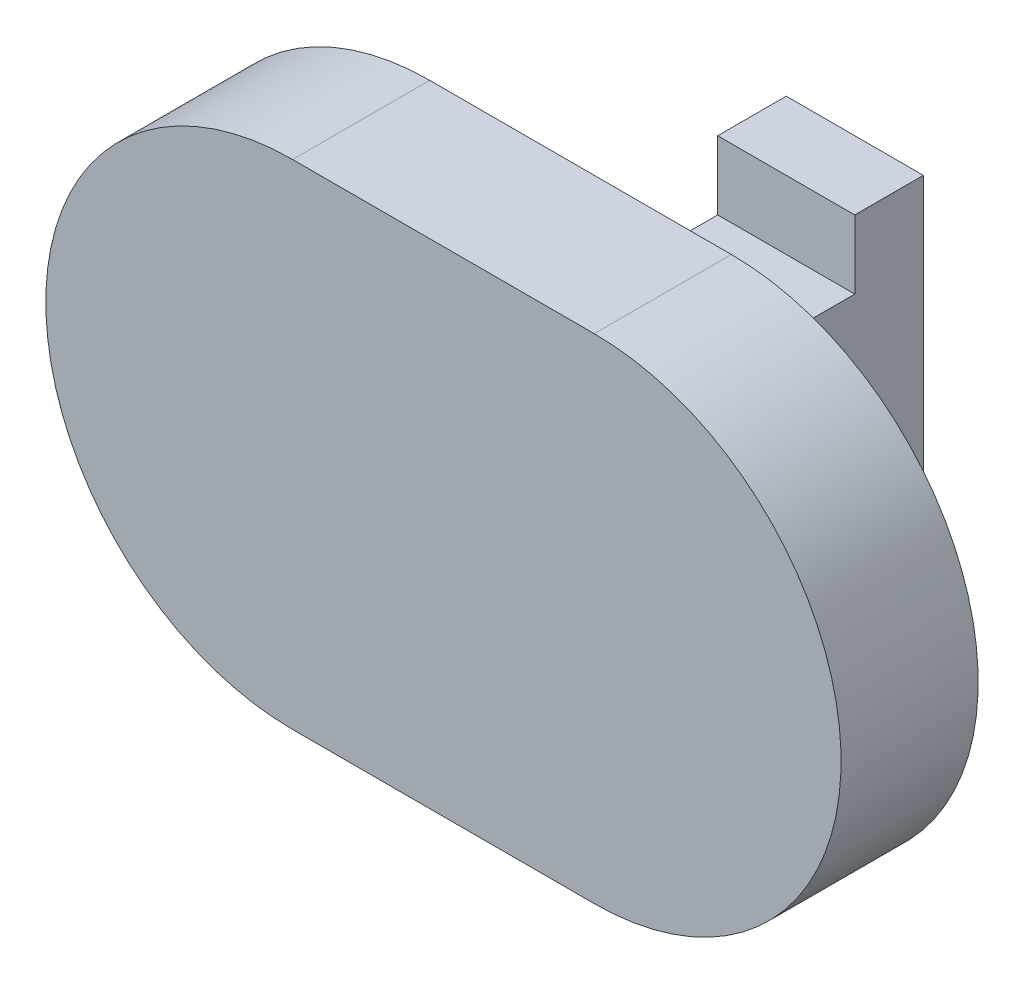
SolidWorks part; units mm, degrees
material "PVC Rigid"
ref_plane "Front Plane" through (0, 0, 0) normal (0, 0, 1) x (1, 0, 0)
ref_plane "Top Plane" through (0, 0, 0) normal (0, 1, 0) x (1, 0, 0)
ref_plane "Right Plane" through (0, 0, 0) normal (1, 0, 0) x (0, 0, -1)
sketch "Sketch3" plane through (0, 0, 0) normal (0, 0, 1) x (1, 0, 0)
  line L0 (-1.397, 0) -> (1.397, 0) construction
  line L1 (-1.397, 2.286) -> (1.397, 2.286)
  line L2 (-1.397, -2.286) -> (1.397, -2.286)
  arc A0 (-1.397, 2.286) -> (-1.397, -2.286) centre (-1.397, 0) ccw
  arc A1 (1.397, -2.286) -> (1.397, 2.286) centre (1.397, 0) ccw
  point P2 (0, 0)
  dimension "D1" = 2.286
  dimension "D2" = 2.794
extrude "Boss-Extrude1" add sketch "Sketch3" against normal blind 1.27
sketch "Sketch5" plane through (0, 0, -1.27) normal (0, 0, -1) x (-1, 0, 0)
  line L1 (0.635, 0.635) -> (-0.635, 0.635)
  line L2 (0.635, 0.635) -> (0.635, -0.635)
  line L3 (0.635, -0.635) -> (-0.635, -0.635)
  line L4 (-0.635, 0.635) -> (-0.635, -0.635)
  line L5 (0.635, 0.635) -> (-0.635, -0.635) construction
  line L6 (0.635, -0.635) -> (-0.635, 0.635) construction
  point P0 (0, 0)
  dimension "D1" = 1.27
  dimension "D2" = 1.27
extrude "Boss-Extrude2" add sketch "Sketch5" along normal blind 1.905
sketch "Sketch6" plane through (0, 0, -3.175) normal (0, 0, -1) x (-1, 0, 0)
  line L1 (0.635, -1.27) -> (-0.635, -1.27)
  line L2 (0.635, -1.27) -> (0.635, 1.27)
  line L3 (0.635, 1.27) -> (-0.635, 1.27)
  line L4 (-0.635, -1.27) -> (-0.635, 1.27)
  line L5 (0.635, -1.27) -> (-0.635, 1.27) construction
  line L6 (0.635, 1.27) -> (-0.635, -1.27) construction
  point P0 (0, 0)
  dimension "D1" = 1.27
  dimension "D2" = 2.54
extrude "Boss-Extrude3" add sketch "Sketch6" along normal blind 0.635
